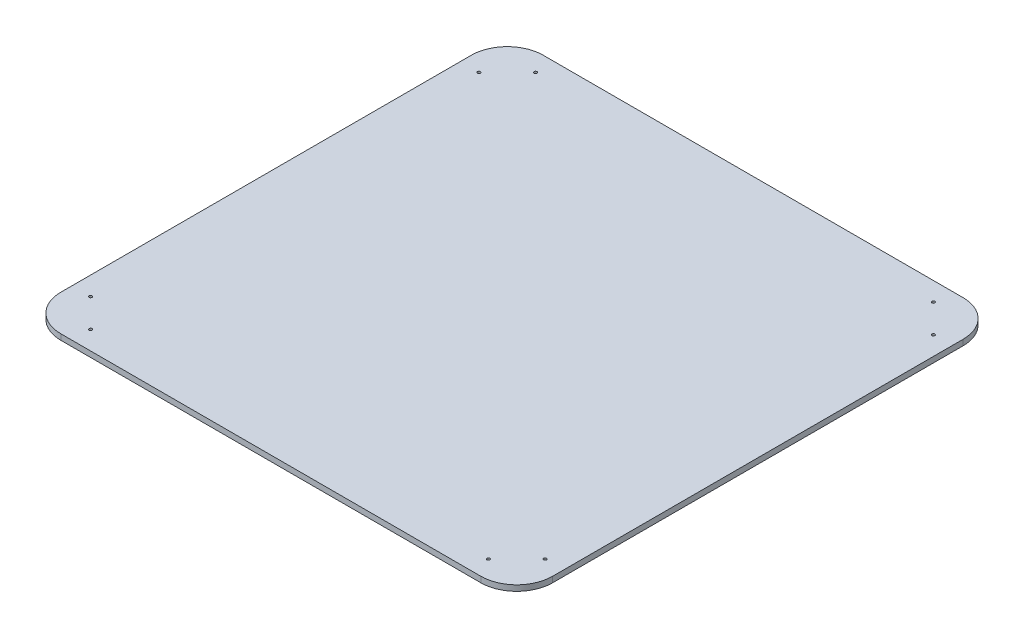
SolidWorks part; units mm, degrees
ref_plane "Alzado" through (0, 0, 0) normal (0, 0, 1) x (1, 0, 0)
ref_plane "Planta" through (0, 0, 0) normal (0, 1, 0) x (1, 0, 0)
ref_plane "Vista lateral" through (0, 0, 0) normal (1, 0, 0) x (0, 0, -1)
sketch "Croquis1" plane through (0, 0, 0) normal (0, 1, 0) x (1, 0, 0)
  line L1 (0, 0) -> (520, 0)
  line L2 (0, 0) -> (0, 510)
  line L3 (0, 510) -> (520, 510)
  line L4 (520, 0) -> (520, 510)
  dimension "D1" = 520
  dimension "D2" = 510
extrude "Saliente-Extruir1" add sketch "Croquis1" along normal blind 6
sketch "Croquis2" plane through (0, 6, 0) normal (0, 1, 0) x (1, 0, 0)
  line L0 (0, 510) -> (0, 0) construction
  line L1 (520, 510) -> (0, 510) construction
  line L2 (520, 255) -> (0, 255) construction
  line L3 (520, 0) -> (520, 510) construction
  line L4 (0, 0) -> (520, 0) construction
  line L5 (260, 510) -> (260, 0) construction
  line L6 (0, 510) -> (0, 0) construction
  circle A0 centre (19.75, 490.25) radius 4.05 construction
  circle A1 centre (19.75, 19.75) radius 4.05 construction
  circle A2 centre (500.25, 19.75) radius 4.05 construction
  circle A3 centre (500.25, 490.25) radius 4.05 construction
  circle A4 centre (470.25, 490.25) radius 1.55
  circle A6 centre (500.25, 460.25) radius 1.55
  circle A7 centre (500.25, 49.75) radius 1.55
  circle A8 centre (19.75, 460.25) radius 1.55
  circle A9 centre (19.75, 49.75) radius 1.55
  circle A17 centre (470.25, 19.75) radius 1.55
  circle A28 centre (49.75, 490.25) radius 1.55
  circle A35 centre (485.25, 475.25) radius 4.05 construction
  circle A36 centre (34.7523, 34.7523) radius 4.05 construction
  circle A37 centre (49.75, 19.75) radius 1.55
  circle A38 centre (34.75, 475.25) radius 4.05 construction
  circle A47 centre (485.2477, 34.7523) radius 4.05 construction
  dimension "D1" = 8.1
  dimension "D5" = 19.75
  dimension "D3" = 19.75
  dimension "D6" = 3.1
  dimension "D2" = 19.75
  dimension "D4" = 19.75
  dimension "D7" = 30
  dimension "D8" = 30
  dimension "D20" = 15
  dimension "D21" = 15
  dimension "D22" = 15.0023
  dimension "D23" = 15.0023
  dimension "D24" = 30
  dimension "D25" = 30
extrude "Cortar-Extruir1" cut sketch "Croquis2" against normal up to surface (6 mm away) up to face at (260, 0, -255)
fillet "Redondeo1" radius 38 4 edges at (0, 3, -510) (520, 3, -510) (520, 3, 0) (0, 3, 0)
